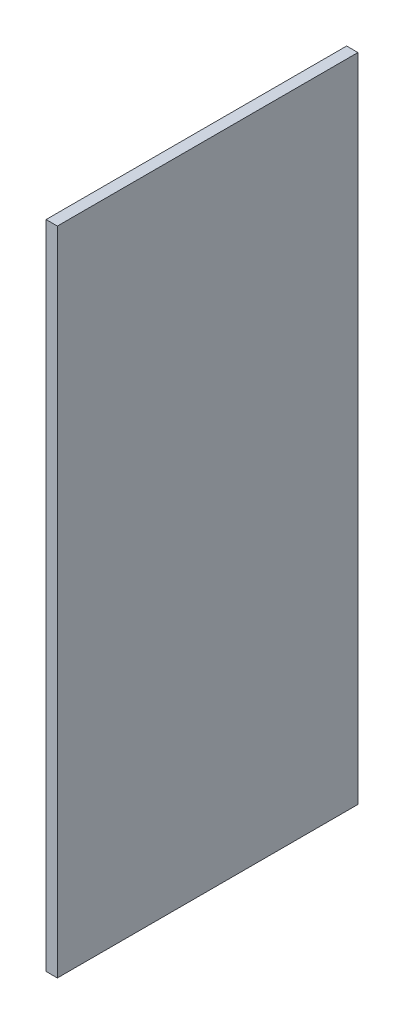
SolidWorks part; units mm, degrees
ref_plane "Front Plane" through (0, 0, 0) normal (0, 0, 1) x (1, 0, 0)
ref_plane "Top Plane" through (0, 0, 0) normal (0, 1, 0) x (1, 0, 0)
ref_plane "Right Plane" through (0, 0, 0) normal (1, 0, 0) x (0, 0, -1)
other "Configuration Table"
sketch "Sketch1" plane through (0, 0, 0) normal (0, 0, 1) x (1, 0, 0)
  line L1 (668.5, 120) -> (698.5, 120)
  line L2 (668.5, 120) -> (668.5, 1850)
  line L3 (668.5, 1850) -> (698.5, 1850)
  line L4 (698.5, 120) -> (698.5, 1850)
extrude "OVEN_yalitim_tasyunu_sag_1" add sketch "Sketch1" against normal blind 798.5 from offset 20 separate body
